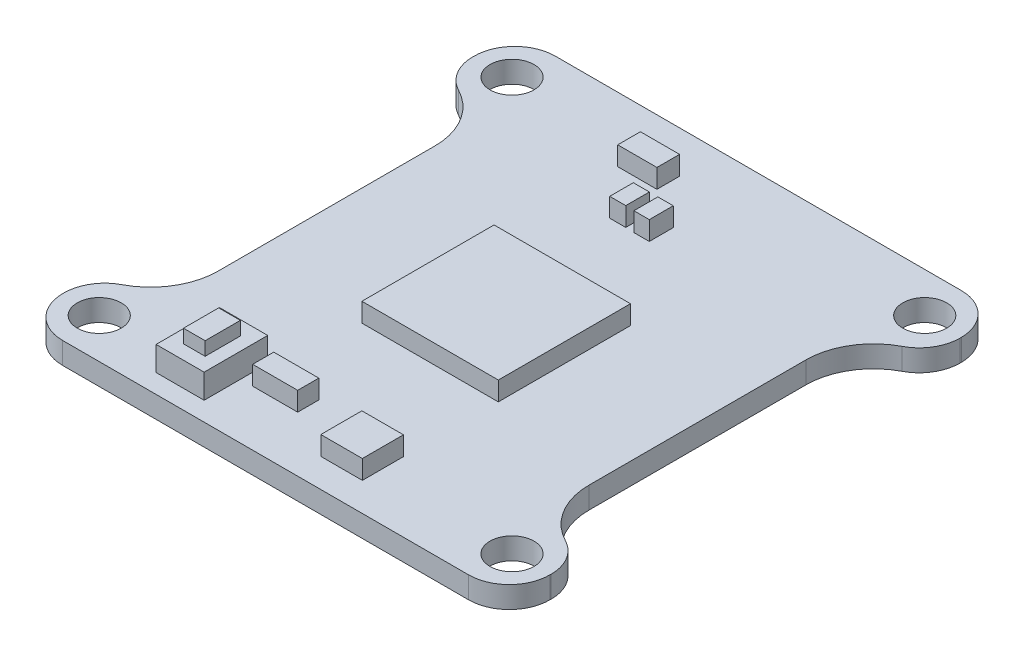
SolidWorks part; units mm, degrees
ref_plane "Front Plane" through (0, 0, 0) normal (0, 0, 1) x (1, 0, 0)
ref_plane "Top Plane" through (0, 0, 0) normal (0, 1, 0) x (1, 0, 0)
ref_plane "Right Plane" through (0, 0, 0) normal (1, 0, 0) x (0, 0, -1)
sketch "Sketch1" plane through (0, 0, 0) normal (0, 1, 0) x (1, 0, 0)
  line L0 (0, 18.2) -> (0, -18.2) construction
  line L1 (-18, 18.2) -> (18, 18.2)
  line L2 (-18, 18.2) -> (-18, -18.2)
  line L3 (-18, -18.2) -> (18, -18.2)
  line L4 (18, 18.2) -> (18, -18.2)
  line L5 (-18, 18.2) -> (18, -18.2) construction
  line L6 (-18, -18.2) -> (18, 18.2) construction
  line L7 (13.7, 18.2) -> (-13.7, 18.2)
  line L8 (13.7, 18.2) -> (13.7, -18.2)
  line L9 (13.7, -18.2) -> (-13.7, -18.2)
  line L10 (-13.7, 18.2) -> (-13.7, -18.2)
  line L11 (13.7, 18.2) -> (-13.7, -18.2) construction
  line L12 (13.7, -18.2) -> (-13.7, 18.2) construction
  line L13 (-18, 0) -> (18, 0) construction
  line L15 (18, 12.1) -> (-18, 12.1)
  line L16 (18, 12.1) -> (18, -12.1)
  line L17 (18, -12.1) -> (-18, -12.1)
  line L18 (-18, 12.1) -> (-18, -12.1)
  line L19 (18, 12.1) -> (-18, -12.1) construction
  line L20 (18, -12.1) -> (-18, 12.1) construction
  circle A0 centre (-15.25, 15.25) radius 1.625
  circle A1 centre (15.25, 15.25) radius 1.625
  circle A2 centre (15.25, -15.25) radius 1.625
  circle A3 centre (-15.25, -15.25) radius 1.625
  point P0 (0, 0)
  point P5 (0, 0)
  point P23 (0, 0)
  dimension "D4" = 3.25
  dimension "D1" = 36.4
  dimension "D2" = 36
  dimension "D3" = 27.4
  dimension "D5" = 30.5
  dimension "D6" = 30.5
  dimension "D7" = 24.2
extrude "PCB" add sketch "Sketch1" along normal blind 1.6 contours L15 L8 L1 L10 | L17 L8 L15 L10 | L4 L17 L8 L3 A2 | L8 L17 L10 L3 | L10 L17 L2 L3 A3 | L15 L4 L1 L8 A1 | L15 L10 L1 L2 A0
sketch "Sketch2" plane through (0, 1.6, 0) normal (0, 1, 0) x (1, 0, 0)
  line L1 (-5.0578, -6.0345) -> (5.023, -6.0345)
  line L2 (-5.0578, -6.0345) -> (-5.0578, 3.7323)
  line L3 (-5.0578, 3.7323) -> (5.023, 3.7323)
  line L4 (5.023, -6.0345) -> (5.023, 3.7323)
  line L5 (1.9534, -13.0458) -> (5.023, -13.0458)
  line L6 (1.9534, -13.0458) -> (1.9534, -16.0805)
  line L7 (1.9534, -16.0805) -> (5.023, -16.0805)
  line L8 (5.023, -13.0458) -> (5.023, -16.0805)
  line L9 (-5.616, 15.1038) -> (-2.7208, 15.1038)
  line L10 (-5.616, 15.1038) -> (-5.616, 13.4294)
  line L11 (-5.616, 13.4294) -> (-2.7208, 13.4294)
  line L12 (-2.7208, 15.1038) -> (-2.7208, 13.4294)
  line L13 (-2.6161, 11.5807) -> (-1.4301, 11.5807)
  line L14 (-2.6161, 11.5807) -> (-2.6161, 9.8366)
  line L15 (-2.6161, 9.8366) -> (-1.4301, 9.8366)
  line L16 (-1.4301, 11.5807) -> (-1.4301, 9.8366)
  line L17 (-0.8023, 11.5807) -> (0.3353, 11.5807)
  line L18 (-0.8023, 11.5807) -> (-0.8023, 9.8089)
  line L19 (-0.8023, 9.8089) -> (0.3353, 9.8089)
  line L20 (0.3353, 11.5807) -> (0.3353, 9.8089)
  line L21 (-1.7319, -12.5448) -> (-5.0578, -12.5448)
  line L22 (-1.7319, -12.5448) -> (-1.7319, -14.1049)
  line L23 (-1.7319, -14.1049) -> (-5.0578, -14.1049)
  line L24 (-5.0578, -12.5448) -> (-5.0578, -14.1049)
extrude "Top components" add sketch "Sketch2" along normal blind 1.4
fillet "Fillet1" radius 3 8 edges at (-18, 0.8, 12.1) (-18, 0.8, -12.1) (18, 0.8, -12.1) (18, 0.8, 12.1) (18, 0.8, 18.2) (-18, 0.8, 18.2) (-18, 0.8, -18.2) (18, 0.8, -18.2)
fillet "Fillet2" radius 5 4 edges at (13.7, 0.8, -12.1) (13.7, 0.8, 12.1) (-13.7, 0.8, 12.1) (-13.7, 0.8, -12.1)
sketch "Sketch3" plane through (0, 0, 0) normal (0, -1, 0) x (1, 0, 0)
  line L1 (-9.9064, -12.8365) -> (-6.7322, -12.8365)
  line L2 (-9.9064, -12.8365) -> (-9.9064, -15.8014)
  line L3 (-9.9064, -15.8014) -> (-6.7322, -15.8014)
  line L4 (-6.7322, -12.8365) -> (-6.7322, -15.8014)
  line L5 (-5.8601, -13.3597) -> (-2.7557, -13.3597)
  line L6 (-5.8601, -13.3597) -> (-5.8601, -14.8945)
  line L7 (-5.8601, -14.8945) -> (-2.7557, -14.8945)
  line L8 (-2.7557, -13.3597) -> (-2.7557, -14.8945)
  line L9 (2.1627, 10.325) -> (5.1625, 10.325)
  line L10 (2.1627, 10.325) -> (2.1627, 8.7553)
  line L11 (2.1627, 8.7553) -> (5.1625, 8.7553)
  line L12 (5.1625, 10.325) -> (5.1625, 8.7553)
  line L13 (-4.7788, 10.918) -> (-3.5231, 10.918)
  line L14 (-4.7788, 10.918) -> (-4.7788, 8.0228)
  line L15 (-4.7788, 8.0228) -> (-3.5231, 8.0228)
  line L16 (-3.5231, 10.918) -> (-3.5231, 8.0228)
  line L17 (-0.9767, -13.3597) -> (-2.1278, -13.3597)
  line L18 (-0.9767, -13.3597) -> (-0.9767, -15.4177)
  line L19 (-0.9767, -15.4177) -> (-2.1278, -15.4177)
  line L20 (-2.1278, -13.3597) -> (-2.1278, -15.4177)
extrude "Rear components" add sketch "Sketch3" along normal blind 1.4
sketch "Sketch4" plane through (0, 1.6, 0) normal (0, 1, 0) x (1, 0, 0)
  line L0 (-15, -18.2) -> (15, -18.2) construction
  line L1 (-9.5, -12.1) -> (-5.95, -12.1)
  line L2 (-9.5, -12.1) -> (-9.5, -16.8)
  line L3 (-9.5, -16.8) -> (-5.95, -16.8)
  line L4 (-5.95, -12.1) -> (-5.95, -16.8)
  dimension "D1" = 3.55
  dimension "D2" = 4.7
  dimension "D3" = 8.5
  dimension "D4" = 1.4
extrude "Button base" add sketch "Sketch4" along normal blind 1.8
sketch "Sketch5" plane through (0, 3.4, 0) normal (0, 1, 0) x (1, 0, 0)
  line L0 (-9.5, -12.1) -> (-5.95, -16.8) construction
  line L2 (-8.525, -13.15) -> (-6.925, -13.15)
  line L3 (-8.525, -13.15) -> (-8.525, -15.75)
  line L4 (-8.525, -15.75) -> (-6.925, -15.75)
  line L5 (-6.925, -13.15) -> (-6.925, -15.75)
  line L6 (-8.525, -13.15) -> (-6.925, -15.75) construction
  line L7 (-8.525, -15.75) -> (-6.925, -13.15) construction
  point P4 (-7.725, -14.45)
  dimension "D1" = 1.6
  dimension "D2" = 2.6
extrude "Button tip" add sketch "Sketch5" along normal blind 1
